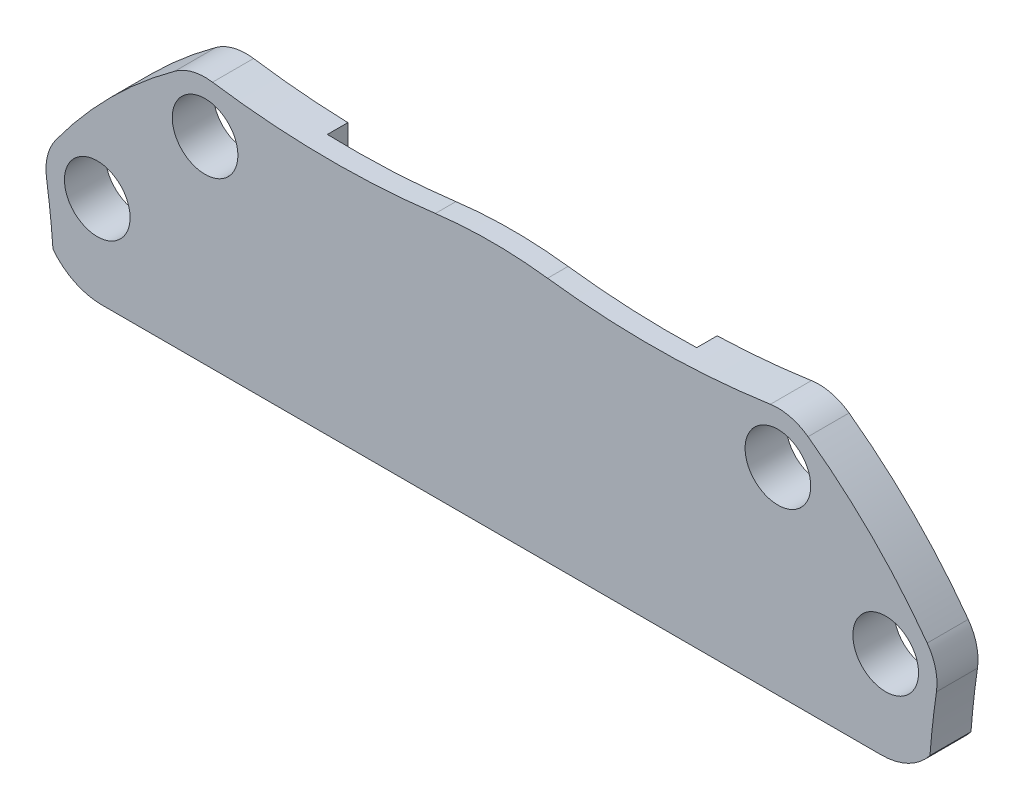
SolidWorks part; units mm, degrees
ref_plane "前视基准面" through (0, 0, 0) normal (0, 0, 1) x (1, 0, 0)
ref_plane "上视基准面" through (0, 0, 0) normal (0, 1, 0) x (1, 0, 0)
ref_plane "右视基准面" through (0, 0, 0) normal (1, 0, 0) x (0, 0, -1)
other "Configuration Table"
sketch "草图1" plane through (0, 0, 0) normal (0, 0, 1) x (1, 0, 0)
  line L0 (-28.2831, 0) -> (22.8761, 0) construction
  line L1 (0, 16.4292) -> (0, -22.0442) construction
  line L2 (19.2142, 13.9599) -> (0, 0)
  line L3 (0, 0) -> (13.9599, 19.2142)
  line L4 (13.9599, 23.587) -> (13.9599, 19.2142) construction
  line L5 (-19, 23.587) -> (19, 23.587)
  line L6 (-22, 20.587) -> (-22, 12.587)
  line L7 (-19, 9.587) -> (19, 9.587)
  line L8 (22, 20.587) -> (22, 12.587)
  line L9 (19.2142, 13.9599) -> (19.2142, 9.587) construction
  circle A0 centre (0, 0) radius 23.75 construction
  circle A1 centre (19.2142, 13.9599) radius 1.6
  circle A2 centre (13.9599, 19.2142) radius 1.6
  circle A3 centre (-13.9599, 19.2142) radius 1.6
  circle A4 centre (-19.2142, 13.9599) radius 1.6
  arc A5 (19, 9.587) -> (22, 12.587) centre (19, 12.587) ccw
  arc A6 (-19, 23.587) -> (-22, 20.587) centre (-19, 20.587) ccw
  arc A7 (-22, 12.587) -> (-19, 9.587) centre (-19, 12.587) ccw
  arc A8 (19, 23.587) -> (22, 20.587) centre (19, 20.587) cw
  point P23 (22, 9.587)
  point P26 (-22, 23.587)
  point P31 (22, 23.587)
  dimension "D1" = 47.5
  dimension "D4" = 3.2
  dimension "D7" = 3
  dimension "D2" = 18
  dimension "D3" = 36
  dimension "D5" = 14
  dimension "D6" = 44
extrude "凸台-拉伸1" add sketch "草图1" along normal blind 2
sketch "草图2" plane through (0, 9.587, 0) normal (0, -1, 0) x (1, 0, 0)
  line L0 (-19, 0) -> (19, 0) construction
  line L1 (-9, 0) -> (9, 0)
  line L2 (-9, 0) -> (-9, 1)
  line L3 (-9, 1) -> (9, 1)
  line L4 (9, 0) -> (9, 1)
  line L5 (0, 6.1274) -> (0, -5.3874) construction
  dimension "D1" = 18
  dimension "D2" = 1
extrude "切除-拉伸1" cut sketch "草图2" against normal through all
sketch "草图3" plane through (0, 0, 2) normal (0, 0, 1) x (1, 0, 0)
  line L4 (-19, 9.587) -> (19, 9.587)
  line L5 (22, 12.587) -> (22, 20.587)
  line L6 (19, 23.587) -> (-19, 23.587)
  line L7 (-22, 20.587) -> (-22, 12.587)
  line L9 (22, 12.587) -> (22, 20.587)
  line L10 (19, 23.587) -> (-19, 23.587)
  line L11 (-22, 20.587) -> (-22, 12.587)
  arc A0 (-21.3254, 10.05) -> (-21.6874, 13.5954) centre (-61.26, 7.7635) ccw construction
  arc A1 (15.4294, 21.2367) -> (13.5954, 21.6874) centre (13.9599, 19.2142) ccw construction
  arc A2 (2.7345, 21.5774) -> (13.5954, 21.6874) centre (7.7635, 61.26) ccw construction
  arc A3 (2.7345, 21.5774) -> (-2.7345, 21.5774) centre (0, 0) ccw construction
  arc A4 (-13.5954, 21.6874) -> (-2.7345, 21.5774) centre (-7.7635, 61.26) ccw construction
  arc A5 (-13.5954, 21.6874) -> (-15.4294, 21.2367) centre (-13.9599, 19.2142) ccw construction
  arc A6 (-15.4294, 21.2367) -> (-21.2367, 15.4294) centre (0, 0) ccw construction
  arc A7 (-21.2367, 15.4294) -> (-21.6874, 13.5954) centre (-19.2142, 13.9599) ccw construction
  arc A8 (15.4294, 21.2367) -> (13.5954, 21.6874) centre (13.9599, 19.2142) ccw
  arc A9 (2.7345, 21.5774) -> (13.5954, 21.6874) centre (7.7635, 61.26) ccw
  arc A10 (2.7345, 21.5774) -> (-2.7345, 21.5774) centre (0, 0) ccw
  arc A11 (-13.5954, 21.6874) -> (-2.7345, 21.5774) centre (-7.7635, 61.26) ccw
  arc A12 (-13.5954, 21.6874) -> (-15.4294, 21.2367) centre (-13.9599, 19.2142) ccw
  arc A13 (-15.4294, 21.2367) -> (-21.2367, 15.4294) centre (0, 0) ccw
  arc A14 (-21.2367, 15.4294) -> (-21.6874, 13.5954) centre (-19.2142, 13.9599) ccw
  arc A15 (-21.3717, 10.7498) -> (-21.6874, 13.5954) centre (-61.26, 7.7635) ccw
  arc A16 (21.6874, 13.5954) -> (21.3254, 10.05) centre (61.26, 7.7635) ccw construction
  arc A17 (21.6874, 13.5954) -> (21.2367, 15.4294) centre (19.2142, 13.9599) ccw construction
  arc A18 (21.2367, 15.4294) -> (15.4294, 21.2367) centre (0, 0) ccw construction
  arc A19 (21.6874, 13.5954) -> (21.3717, 10.7498) centre (61.26, 7.7635) ccw
  arc A20 (21.6874, 13.5954) -> (21.2367, 15.4294) centre (19.2142, 13.9599) ccw
  arc A21 (21.2367, 15.4294) -> (15.4294, 21.2367) centre (0, 0) ccw
  arc A26 (19, 9.587) -> (22, 12.587) centre (19, 12.587) ccw
  arc A27 (22, 20.587) -> (19, 23.587) centre (19, 20.587) ccw
  arc A28 (-19, 23.587) -> (-22, 20.587) centre (-19, 20.587) ccw
  arc A29 (-22, 12.587) -> (-19, 9.587) centre (-19, 12.587) ccw
  arc A30 (21.3717, 10.7498) -> (22, 12.587) centre (19, 12.587) ccw
  arc A31 (22, 20.587) -> (19, 23.587) centre (19, 20.587) ccw
  arc A32 (-19, 23.587) -> (-22, 20.587) centre (-19, 20.587) ccw
  arc A33 (-22, 12.587) -> (-21.3717, 10.7498) centre (-19, 12.587) ccw
  dimension "D1" = 0
extrude "切除-拉伸2" cut sketch "草图3" against normal through all
